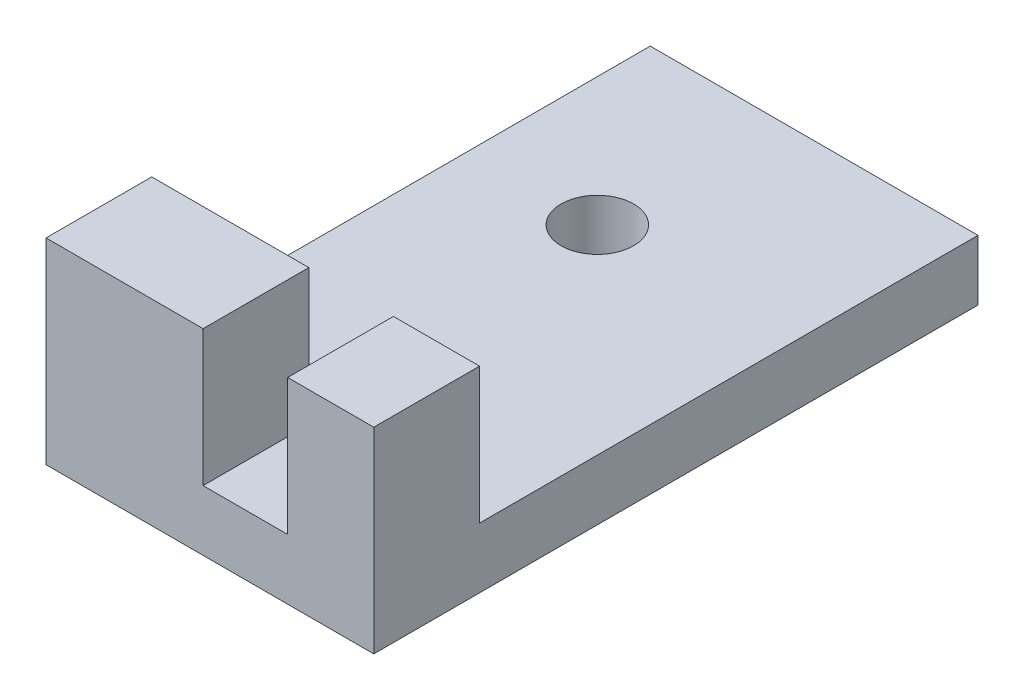
SolidWorks part; units mm, degrees
ref_plane "Front Plane" through (0, 0, 0) normal (0, 0, 1) x (1, 0, 0)
ref_plane "Top Plane" through (0, 0, 0) normal (0, 1, 0) x (1, 0, 0)
ref_plane "Right Plane" through (0, 0, 0) normal (1, 0, 0) x (0, 0, -1)
sketch "Sketch1" plane through (0, 0, 0) normal (0, 1, 0) x (1, 0, 0)
  line L1 (0, 0) -> (21.7, 0)
  line L2 (0, 0) -> (0, -40)
  line L3 (0, -40) -> (21.7, -40)
  line L4 (21.7, 0) -> (21.7, -40)
  dimension "D1" = 40
  dimension "D2" = 21.7
extrude "Boss-Extrude1" add sketch "Sketch1" along normal blind 13
sketch "Sketch3" plane through (0, 13, 0) normal (0, 1, 0) x (1, 0, 0)
  line L0 (21.7, -40) -> (21.7, 0) construction
  line L1 (0, 0) -> (21.7, 0)
  line L2 (0, 0) -> (0, -33)
  line L3 (0, -33) -> (21.7, -33)
  line L4 (21.7, 0) -> (21.7, -33)
  dimension "D1" = 33
extrude "Cut-Extrude1" cut sketch "Sketch3" against normal blind 9
sketch "Sketch5" plane through (0, 0, 33) normal (0, 0, -1) x (-1, 0, 0)
  line L0 (0, 13) -> (-21.7, 13) construction
  line L1 (-16, 13) -> (-10.4, 13)
  line L2 (-16, 13) -> (-16, 4)
  line L3 (-16, 4) -> (-10.4, 4)
  line L4 (-10.4, 13) -> (-10.4, 4)
  line L5 (-21.7, 4) -> (-21.7, 13) construction
  dimension "D1" = 9
  dimension "D2" = 5.7
  dimension "D3" = 5.6
extrude "Cut-Extrude2" cut sketch "Sketch5" against normal through all
sketch "Sketch6" plane through (0, 4, 0) normal (0, 1, 0) x (1, 0, 0)
  line L0 (21.7, 0) -> (0, 0) construction
  line L1 (21.7, -33) -> (21.7, 0) construction
  line L2 (0, 0) -> (0, -33) construction
  circle A0 centre (8.5, -12) radius 2.4
  dimension "D1" = 4.8
  dimension "D2" = 12
  dimension "D3" = 13.2
  dimension "D4" = 8.5
extrude "Cut-Extrude4" cut sketch "Sketch6" against normal through all contours A0
